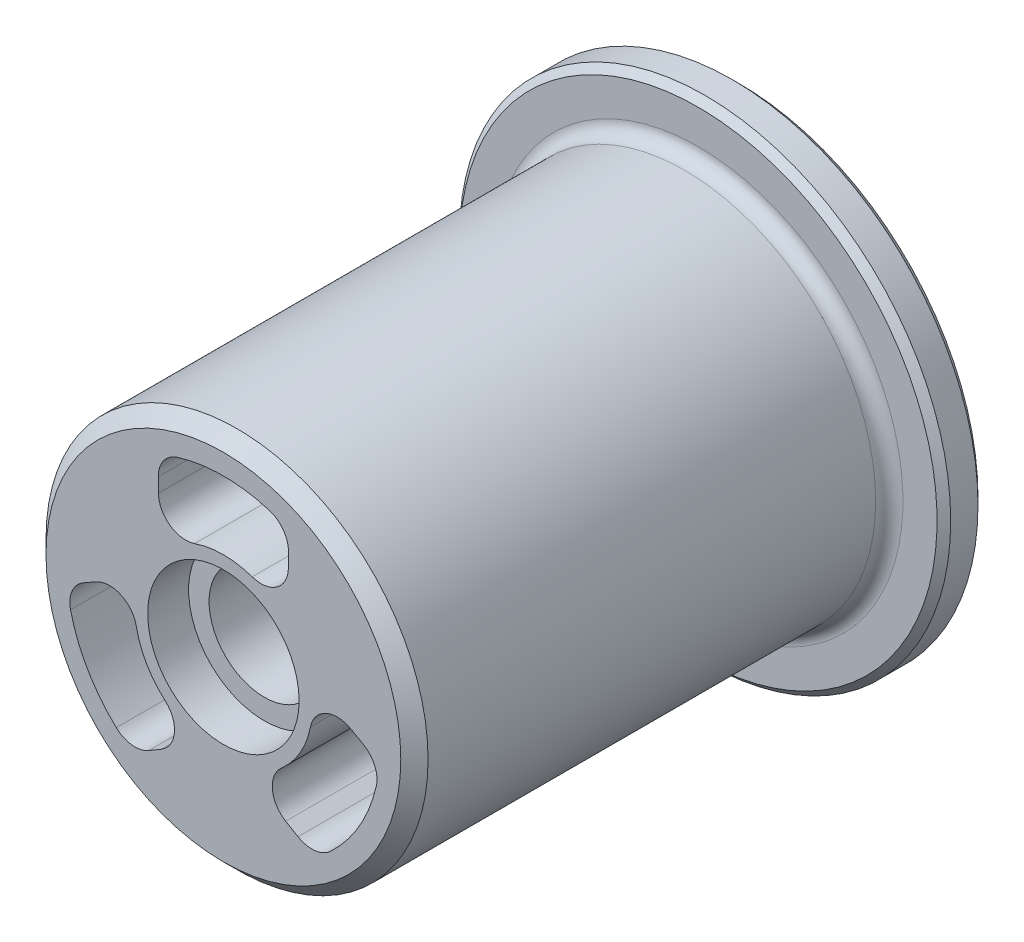
SolidWorks part; units mm, degrees
material "PA Tipo 6"
ref_plane "Alzado" through (0, 0, 0) normal (1, 0, 0) x (0, 1, 0)
ref_plane "Planta" through (0, 0, 0) normal (0, 0, 1) x (0, 1, 0)
ref_plane "Vista lateral" through (0, 0, 0) normal (0, 1, 0) x (-1, 0, 0)
sketch "Croquis1" plane through (0, 0, 0) normal (0, 0, 1) x (0, 1, 0)
  circle A0 centre (0, 0) radius 14
  circle A1 centre (0, 0) radius 4.05
  dimension "D1" = 28
  dimension "D2" = 8.1
extrude "Saliente-Extruir1" add sketch "Croquis1" along normal mid plane 37.8
chamfer "Chaflán1" distance 1 angle 45 1 edges at (14, 0, 18.9)
sketch "Croquis2" plane through (0, 0, 18.9) normal (0, 0, 1) x (1, 0, 0)
  line L0 (0, 6.5) -> (0, 13.4289) construction
  line L1 (4.7295, 4.4589) -> (4.7819, 10.4587)
  line L2 (-4.7295, 4.4589) -> (-4.7819, 10.4587)
  arc A0 (4.7295, 4.4589) -> (-4.7295, 4.4589) centre (0, 0) ccw
  arc A1 (4.7819, 10.4587) -> (-4.7819, 10.4587) centre (0, 0) ccw
  dimension "D1" = 6.5
  dimension "D2" = 11.5
  dimension "D3" = 0.5
  dimension "D4" = 6
extrude "Cortar-Extruir1" cut sketch "Croquis2" against normal up to next
fillet "Redondeo1" radius 2 4 edges at (4.7819, 10.4587, 0) (4.7295, 4.4589, 0) (-4.7295, 4.4589, 0) (-4.7819, 10.4587, 0)
pattern_circular "MatrizC1" count 3 over 360 about axis through (0, 0, 0) along (0, 0, 1) of "Cortar-Extruir1", "Redondeo1"
sketch "Croquis3" plane through (0, 0, 0) normal (0, 1, 0) x (-1, 0, 0)
  line L6 (-4.05, -18.9) -> (4.05, -18.9) construction
  line L7 (0, -18.9) -> (0, 18.9) construction
  line L8 (4.05, 18.9) -> (-4.05, 18.9) construction
  line L9 (-4, -0.4) -> (4, -0.4) construction
  circle A0 centre (0, -0.4) radius 4
  point P0 (0, -0.4)
  dimension "D2" = 8
  dimension "D1" = 18.5
extrude "Cortar-Extruir2" cut sketch "Croquis3" against normal blind 29
sketch "Croquis4" plane through (0, 0, 18.9) normal (0, 0, 1) x (1, 0, 0)
  line L0 (0, 0) -> (-15.604, 9.0089) construction
  line L1 (0, 0) -> (0, 13) construction
  circle A0 centre (0, 0) radius 13 construction
  circle A1 centre (0, 0) radius 11 construction
  point P3 (-9.5263, 5.5)
  point P12 (9.5263, 5.5)
  point P13 (0, -11)
  point P14 (0, 0)
  dimension "D2" = 22
  dimension "D1" = 60
  dimension "D3" = 3
hole_wizard "Taladro roscado M3.5x0.61" [suppressed] positions "Croquis4" profile "Croquis5" tap size "M3.5x0.6" standard "Ansi Metric"
sketch "Croquis5" plane through (0, 0, 18.9) normal (1, 0, 0) x (0, -1, 0)
  line L0 (0, 0) -> (0, 20.8712)
  line L1 (0, 20.8712) -> (1.45, 20)
  line L2 (1.45, 20) -> (1.45, 0)
  line L5 (1.45, 0) -> (0, 0)
  line L10 (0, 20.8712) -> (-1.45, 20) construction
  line L11 (0, -6.35) -> (0, 107.95) construction
  dimension "Diámetro de perforador para roscar" = 2.9
  dimension "Profundidad de perforador para roscar" = 20
  dimension "Ángulo de perforador" = 118
cosmetic thread "Rosca de taladro1" [suppressed] parameters "D1"=7, "D2"=3.5
cosmetic thread "Rosca de taladro2" [suppressed] parameters "D1"=7, "D2"=3.5
cosmetic thread "Rosca de taladro3" [suppressed] parameters "D1"=7, "D2"=3.5
sketch "Croquis6" plane through (0, 0, -18.9) normal (0, 0, -1) x (1, 0, 0)
  line L0 (-10.2395, 0.4042) -> (-9.3273, -0.1119) construction
  line L1 (-4.5667, 8.1337) -> (-5.4698, 8.6656) construction
  line L2 (5.4698, 8.6656) -> (4.5667, 8.1337) construction
  line L3 (9.3273, -0.1119) -> (10.2395, 0.4042) construction
  line L4 (-4.7606, -8.0217) -> (-4.7697, -9.0698) construction
  line L5 (4.7697, -9.0698) -> (4.7606, -8.0217) construction
  line L6 (-10.2395, 0.4042) -> (-9.3273, -0.1119)
  line L7 (-4.5667, 8.1337) -> (-5.4698, 8.6656)
  line L8 (5.4698, 8.6656) -> (4.5667, 8.1337)
  line L9 (9.3273, -0.1119) -> (10.2395, 0.4042)
  line L10 (-4.7606, -8.0217) -> (-4.7697, -9.0698)
  line L11 (4.7697, -9.0698) -> (4.7606, -8.0217)
  arc A0 (-11.2031, 2.5964) -> (-10.2395, 0.4042) centre (-9.2547, 2.1449) ccw construction
  arc A1 (-7.8501, 8.4039) -> (-11.2031, 2.5964) centre (0, 0) ccw construction
  arc A2 (-5.4698, 8.6656) -> (-7.8501, 8.4039) centre (-6.4849, 6.9424) ccw construction
  arc A3 (-4.2684, 4.9021) -> (-6.3795, 1.2455) centre (0, 0) ccw construction
  arc A4 (-4.2684, 4.9021) -> (-4.5667, 8.1337) centre (-5.5818, 6.4104) ccw construction
  arc A5 (7.8501, 8.4039) -> (5.4698, 8.6656) centre (6.4849, 6.9424) ccw construction
  arc A6 (11.2031, 2.5964) -> (7.8501, 8.4039) centre (0, 0) ccw construction
  arc A7 (10.2395, 0.4042) -> (11.2031, 2.5964) centre (9.2547, 2.1449) ccw construction
  arc A8 (-3.3529, -11.0004) -> (3.3529, -11.0004) centre (0, 0) ccw construction
  arc A9 (3.3529, -11.0004) -> (4.7697, -9.0698) centre (2.7698, -9.0872) ccw construction
  arc A10 (-4.7697, -9.0698) -> (-3.3529, -11.0004) centre (-2.7698, -9.0872) ccw construction
  arc A11 (4.7606, -8.0217) -> (2.1111, -6.1476) centre (2.7607, -8.0392) ccw construction
  arc A12 (-2.1111, -6.1476) -> (2.1111, -6.1476) centre (0, 0) ccw construction
  arc A13 (6.3795, 1.2455) -> (9.3273, -0.1119) centre (8.3425, 1.6288) ccw construction
  arc A14 (6.3795, 1.2455) -> (4.2684, 4.9021) centre (0, 0) ccw construction
  arc A15 (4.5667, 8.1337) -> (4.2684, 4.9021) centre (5.5818, 6.4104) ccw construction
  arc A16 (-9.3273, -0.1119) -> (-6.3795, 1.2455) centre (-8.3425, 1.6288) ccw construction
  arc A17 (-2.1111, -6.1476) -> (-4.7606, -8.0217) centre (-2.7607, -8.0392) ccw construction
  circle A18 centre (0, 0) radius 4.05 construction
  arc A20 (-11.2031, 2.5964) -> (-10.2395, 0.4042) centre (-9.2547, 2.1449) ccw
  arc A21 (-7.8501, 8.4039) -> (-11.2031, 2.5964) centre (0, 0) ccw
  arc A22 (-5.4698, 8.6656) -> (-7.8501, 8.4039) centre (-6.4849, 6.9424) ccw
  arc A23 (-4.2684, 4.9021) -> (-6.3795, 1.2455) centre (0, 0) ccw
  arc A24 (-4.2684, 4.9021) -> (-4.5667, 8.1337) centre (-5.5818, 6.4104) ccw
  arc A25 (7.8501, 8.4039) -> (5.4698, 8.6656) centre (6.4849, 6.9424) ccw
  arc A26 (11.2031, 2.5964) -> (7.8501, 8.4039) centre (0, 0) ccw
  arc A27 (10.2395, 0.4042) -> (11.2031, 2.5964) centre (9.2547, 2.1449) ccw
  arc A28 (-3.3529, -11.0004) -> (3.3529, -11.0004) centre (0, 0) ccw
  arc A29 (3.3529, -11.0004) -> (4.7697, -9.0698) centre (2.7698, -9.0872) ccw
  arc A30 (-4.7697, -9.0698) -> (-3.3529, -11.0004) centre (-2.7698, -9.0872) ccw
  arc A31 (4.7606, -8.0217) -> (2.1111, -6.1476) centre (2.7607, -8.0392) ccw
  arc A32 (-2.1111, -6.1476) -> (2.1111, -6.1476) centre (0, 0) ccw
  arc A33 (6.3795, 1.2455) -> (9.3273, -0.1119) centre (8.3425, 1.6288) ccw
  arc A34 (6.3795, 1.2455) -> (4.2684, 4.9021) centre (0, 0) ccw
  arc A35 (4.5667, 8.1337) -> (4.2684, 4.9021) centre (5.5818, 6.4104) ccw
  arc A36 (-9.3273, -0.1119) -> (-6.3795, 1.2455) centre (-8.3425, 1.6288) ccw
  arc A37 (-2.1111, -6.1476) -> (-4.7606, -8.0217) centre (-2.7607, -8.0392) ccw
  circle A38 centre (0, 0) radius 4.05
  circle A40 centre (0, 0) radius 18
  circle A41 centre (0, 0) radius 14 construction
  point P40 (0, 14)
  point P41 (0, 18)
  dimension "D1" = 4
extrude "Saliente-Extruir2" add sketch "Croquis6" against normal blind 3
chamfer "Chaflán2" distance 0.5 angle 45 2 edges at (-18, 0, -15.9) (-18, 0, -18.9)
fillet "Redondeo2" radius 1 1 edges at (-14, 0, -15.9)
ref_plane "Plano1" through (0, 0, 13.9) normal (0, 0, 1) x (1, 0, 0)
sketch "Croquis12" plane through (0, 0, 18.9) normal (0, 0, 1) x (1, 0, 0)
  circle A0 centre (0, 0) radius 5.55
  circle A2 centre (0, 0) radius 4.05 construction
  point P3 (0, -4.05)
  point P4 (0, -5.55)
  dimension "D1" = 1.5
extrude "Cortar-Extruir4" cut sketch "Croquis12" against normal blind 3 contours A0
sketch "Croquis7" plane through (0, 0, 13.9) normal (0, 0, 1) x (1, 0, 0)
  circle A0 centre (0, 0) radius 15 construction
  circle A1 centre (0, 0) radius 15
sketch "Croquis8" plane through (0, 0, 0) normal (0, 1, 0) x (-1, 0, 0)
  line L1 (15, 13.9) -> (-15, 13.9) construction
  line L2 (14, -14.9) -> (14, 17.9) construction
  line L3 (15, 13.9) -> (-15, 13.9) construction
  line L5 (15, 14.4) -> (13, 14.4)
  line L6 (15, 14.4) -> (15, 13.4)
  line L7 (15, 13.4) -> (13, 13.4)
  line L8 (13, 14.4) -> (13, 13.4)
  dimension "D1" = 1
  dimension "D2" = 1
sketch "Croquis10" plane through (0, 0, 18.9) normal (0, 0, 1) x (1, 0, 0)
  line L0 (0, 0) -> (0, 17.5) construction
  line L2 (-0.5, 14) -> (0.5, 14)
  line L3 (-0.5, 14) -> (-0.5, 13)
  line L4 (-0.5, 13) -> (0.5, 13)
  line L5 (0.5, 14) -> (0.5, 13)
  circle A0 centre (0, 0) radius 17.5 construction
  circle A1 centre (0, 0) radius 14 construction
  dimension "D1" = 1
  dimension "D2" = 1
